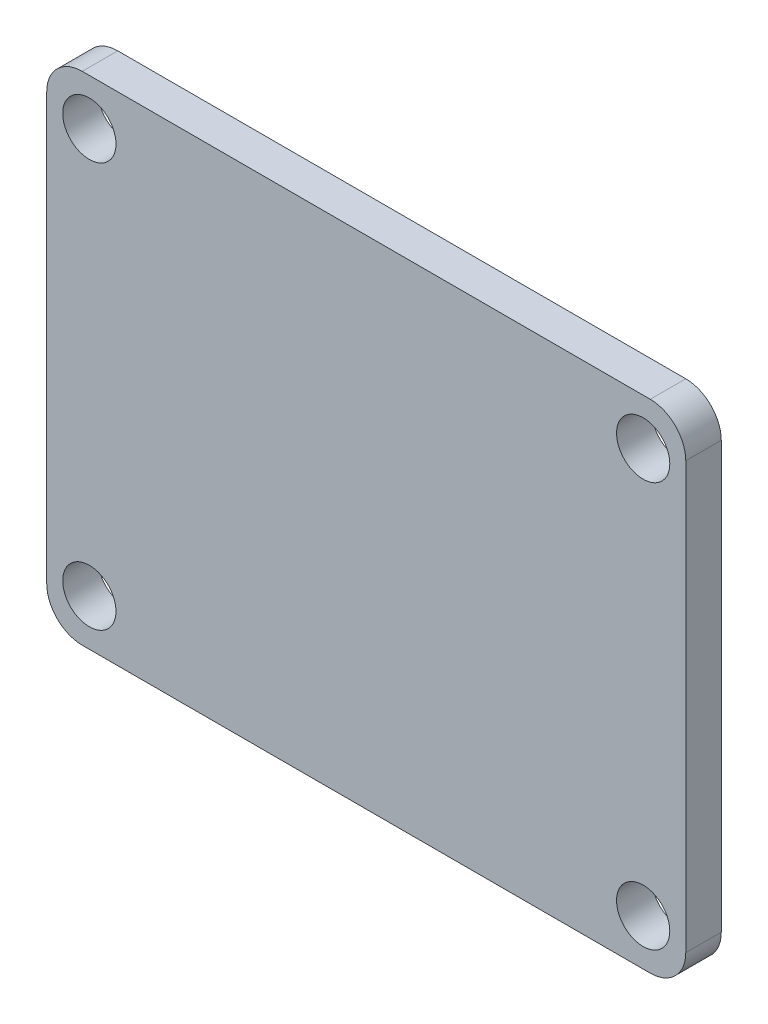
SolidWorks part; units mm, degrees
ref_plane "Front Plane" through (0, 0, 0) normal (0, 0, 1) x (1, 0, 0)
ref_plane "Top Plane" through (0, 0, 0) normal (0, 1, 0) x (1, 0, 0)
ref_plane "Right Plane" through (0, 0, 0) normal (1, 0, 0) x (0, 0, -1)
sketch "Sketch1" plane through (0, 0, 0) normal (0, 0, 1) x (1, 0, 0)
  line L1 (-180, 140) -> (0, 140)
  line L2 (-180, 140) -> (-180, 0)
  line L3 (-180, 0) -> (0, 0)
  line L4 (0, 140) -> (0, 0)
  dimension "D1" = 180
  dimension "D2" = 140
extrude "Boss-Extrude1" add sketch "Sketch1" along normal blind 10
sketch "Sketch2" plane through (0, 0, 10) normal (0, 0, 1) x (1, 0, 0)
  line L0 (-90, -860) -> (-90, 49140) construction
  line L1 (0, 140) -> (-180, 140) construction
  line L2 (-1180, 70) -> (48820, 70) construction
  line L3 (-180, 140) -> (-180, 0) construction
  circle A0 centre (-168, 127) radius 7.5
  circle A1 centre (-12, 127) radius 7.5
  circle A2 centre (-12, 13) radius 7.5
  circle A3 centre (-168, 13) radius 7.5
  point P13 (-90, 140)
  point P18 (-180, 70)
  dimension "D1" = 15
  dimension "D2" = 57
  dimension "D3" = 78
extrude "Cut-Extrude1" cut sketch "Sketch2" against normal through all
fillet "Fillet1" radius 10 4 edges at (0, 0, 5) (0, 140, 5) (-180, 140, 5) (-180, 0, 5)
